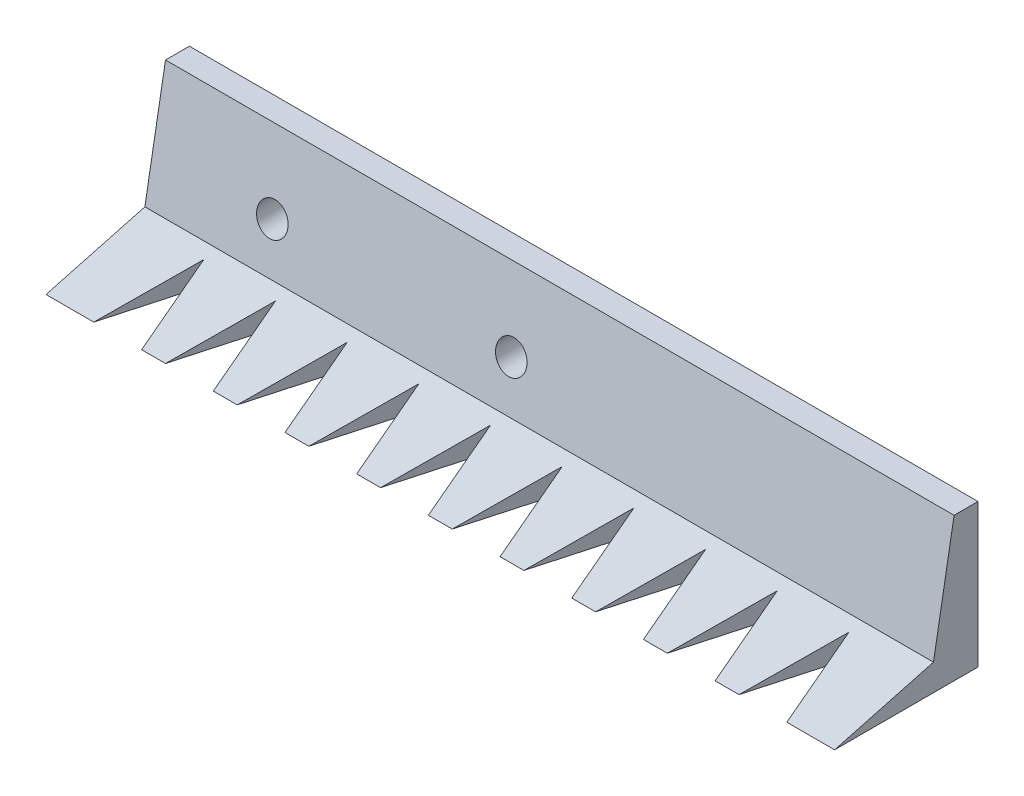
SolidWorks part; units mm, degrees
ref_plane "Front Plane" through (0, 0, 0) normal (0, 0, 1) x (1, 0, 0)
ref_plane "Top Plane" through (0, 0, 0) normal (0, 1, 0) x (1, 0, 0)
ref_plane "Right Plane" through (0, 0, 0) normal (1, 0, 0) x (0, 0, -1)
sketch "Sketch1" plane through (0, 0, 0) normal (1, 0, 0) x (0, 0, -1)
  line L0 (0, 0) -> (0, 30)
  line L3 (-30, 0) -> (0, 0)
  line L4 (-30, 0) -> (-9.3124, 5.5432)
  line L5 (-9.3124, 5.5432) -> (-5, 30)
  line L6 (-5, 30) -> (0, 30)
  dimension "D1" = 30
  dimension "D2" = 30
  dimension "D3" = 10
  dimension "D4" = 15
  dimension "D5" = 5
extrude "Boss-Extrude1" add sketch "Sketch1" along normal blind 100
sketch "Sketch2" plane through (0, 0, 0) normal (0, 0, -1) x (-1, 0, 0)
  line L0 (-100, 15) -> (0, 15) construction
  line L1 (-100, 0) -> (-100, 30) construction
  line L2 (0, 0) -> (0, 30) construction
  line L3 (-100, 30) -> (0, 30) construction
  point P8 (-75, 15)
  point P9 (-25, 15)
  dimension "D1" = 15
  dimension "D2" = 25
  dimension "D3" = 25
hole_wizard "M3 Clearance Hole1" positions "Sketch2" profile "Sketch3" hole size "M3" standard "ANSI Metric" end condition through all
sketch "Sketch3" plane through (25, 15, 0) normal (1, 0, 0) x (0, 1, 0)
  line L0 (0, 0) -> (0, 30)
  line L1 (0, 30) -> (1.7, 30)
  line L2 (1.7, 30) -> (1.7, 0)
  line L5 (1.7, 0) -> (0, 0)
  line L11 (0, -6.35) -> (0, 107.95) construction
  dimension "Thru Hole Dia." = 3.4
  dimension "Thru Hole Depth" = 30
ref_plane "Plane1" through (0, 0, 2.5) normal (0, 0, -1) x (-1, 0, 0)
sketch "Sketch4" plane through (0, 0, 2.5) normal (0, 0, -1) x (-1, 0, 0)
  circle A0 centre (-75, 15) radius 3.25
  circle A1 centre (-25, 15) radius 3.25
  dimension "D1" = 6.5
extrude "Cut-Extrude1" cut sketch "Sketch4" against normal through all
sketch "Sketch6" plane through (100, 0, 0) normal (-1, 0, 0) x (0, 0, 1)
  line L5 (0, 0) -> (30, 0)
  line L6 (30, 0) -> (9.3124, 5.5432)
  line L7 (9.3124, 5.5432) -> (5, 30)
  line L8 (5, 30) -> (0, 30)
  line L9 (0, 30) -> (0, 0)
  line L10 (0, 0) -> (30, 0)
  line L11 (30, 0) -> (9.3124, 5.5432)
  line L12 (9.3124, 5.5432) -> (5, 30)
  line L13 (5, 30) -> (0, 30)
  line L14 (0, 30) -> (0, 0)
  dimension "D1" = 0
extrude "Boss-Extrude2" add sketch "Sketch6" against normal blind 65
sketch "Sketch8" plane through (0, 0, 0) normal (0, 1, 0) x (1, 0, 0)
  line L0 (10, -30) -> (15, -12)
  line L1 (165, -30) -> (0, -30) construction
  line L2 (15, -12) -> (20, -30)
  line L3 (20, -30) -> (10, -30)
  dimension "D1" = 10
  dimension "D2" = 10
  dimension "D3" = 18
extrude "Cut-Extrude2" cut sketch "Sketch8" along normal through all both and the other way through all
pattern_linear "LPattern1" count 10 spacing 15 along (1, 0, 0) of "Cut-Extrude2"
